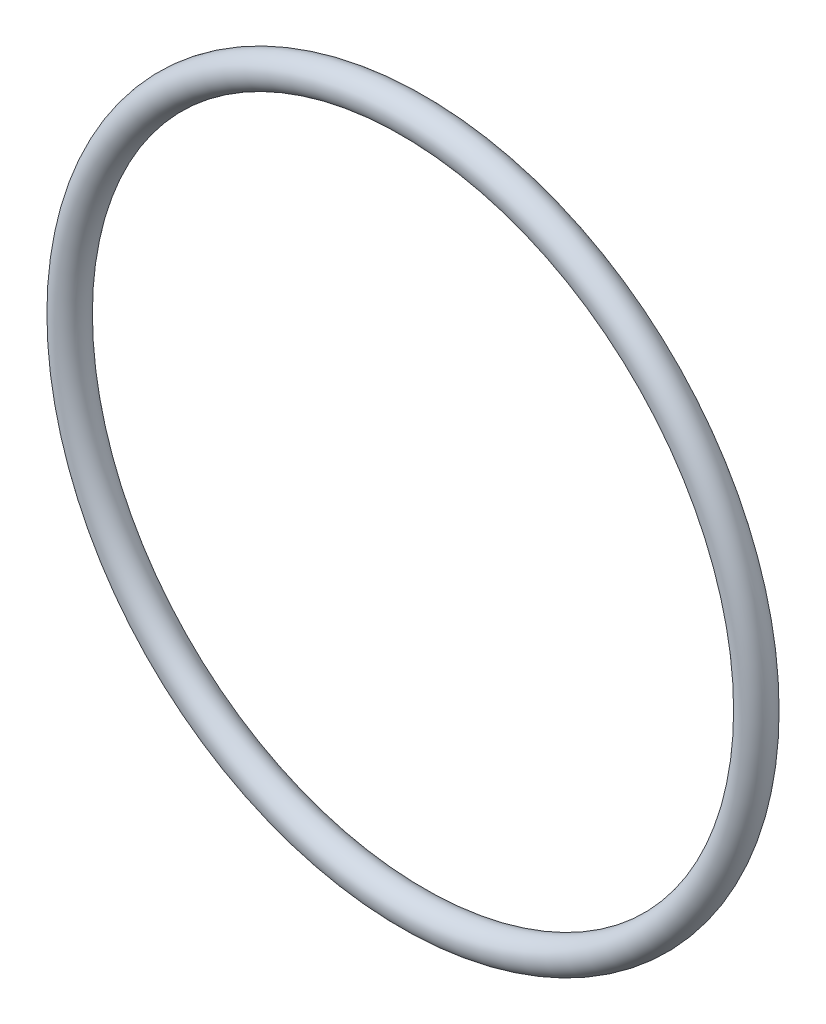
SolidWorks part; units mm, degrees
material "Borracha"
ref_plane "Plano frontal" through (0, 0, 0) normal (0, 0, 1) x (1, 0, 0)
ref_plane "Plano superior" through (0, 0, 0) normal (0, 1, 0) x (1, 0, 0)
ref_plane "Plano direito" through (0, 0, 0) normal (1, 0, 0) x (0, 0, -1)
ref_plane "Plano1" through (0, -32.5, 0) normal (0, 1, 0) x (1, 0, 0)
ref_plane "Plano2" through (0, 0, 1.5) normal (0, 0, 1) x (1, 0, 0)
ref_axis "Eixo1" through (0, -32.5, -88.99) along (0, 0, 1)
sketch "Esboço2" plane through (0, 0, 0) normal (1, 0, 0) x (0, 0, -1)
  line L1 (88.99, -32.5) -> (-88.99, -32.5) construction
  circle A0 centre (0, -0.5) radius 1.5
  dimension "D1" = 30.5
  dimension "D2" = 3
revolve "Revolução1" add sketch "Esboço2" angle 360 about axis through (0, -32.5, -88.99) along (0, 0, 1)
